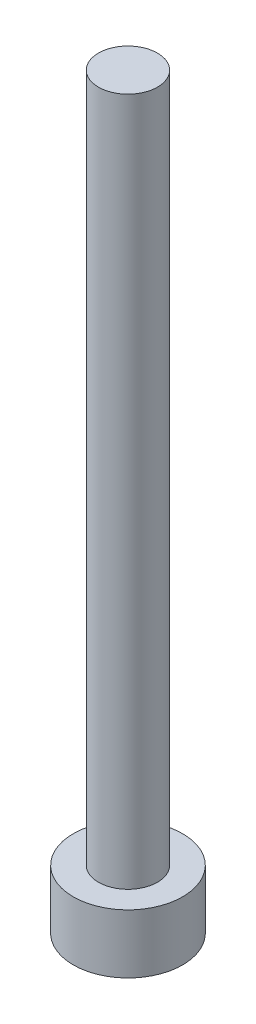
SolidWorks part; units mm, degrees
ref_plane "Front Plane" through (0, 0, 0) normal (0, 0, 1) x (1, 0, 0)
ref_plane "Top Plane" through (0, 0, 0) normal (0, 1, 0) x (1, 0, 0)
ref_plane "Right Plane" through (0, 0, 0) normal (1, 0, 0) x (0, 0, -1)
sketch "Sketch1" plane through (0, 0, 0) normal (0, 1, 0) x (1, 0, 0)
  circle A0 centre (0, 0) radius 2.78
  dimension "D1" = 5.56
extrude "Boss-Extrude1" add sketch "Sketch1" along normal blind 3
sketch "Sketch2" plane through (0, 3, 0) normal (0, 1, 0) x (1, 0, 0)
  circle A0 centre (0, 0) radius 1.5
  dimension "D1" = 3
extrude "Boss-Extrude2" add sketch "Sketch2" along normal blind 35
